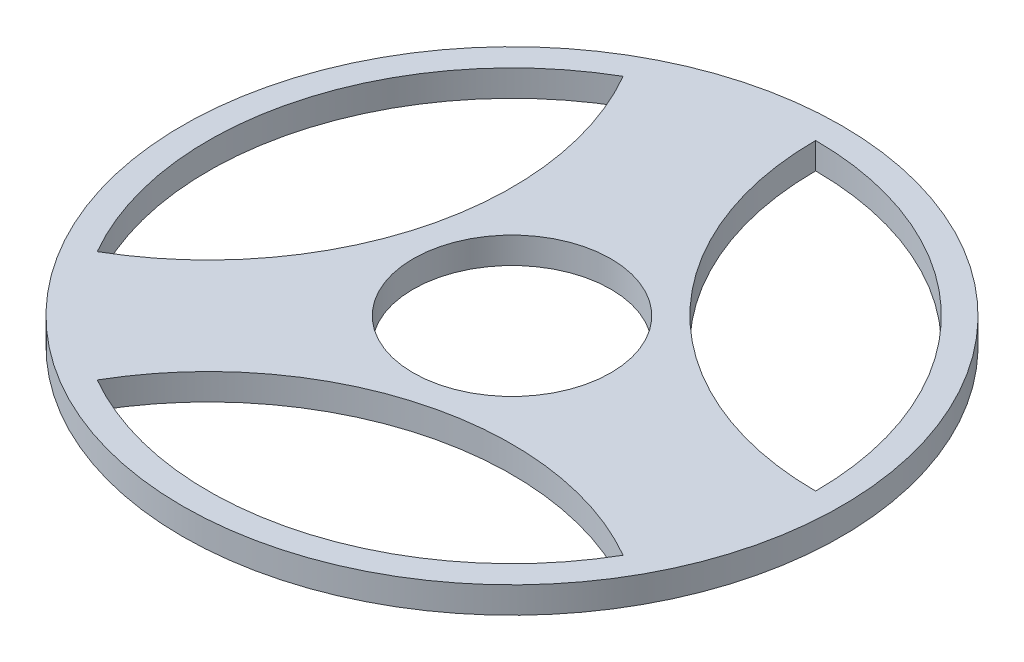
SolidWorks part; units mm, degrees
ref_plane "Alzado" through (0, 0, 0) normal (0, 0, 1) x (1, 0, 0)
ref_plane "Planta" through (0, 0, 0) normal (0, 1, 0) x (1, 0, 0)
ref_plane "Vista lateral" through (0, 0, 0) normal (1, 0, 0) x (0, 0, -1)
sketch "Croquis1" plane through (0, 0, 0) normal (0, 1, 0) x (1, 0, 0)
  line L0 (0, 0) -> (0, 150) construction
  line L2 (0, 500) -> (0, 542.3497) construction
  line L28 (0, 0) -> (460.6468, 0) construction
  line L29 (460.6468, 0) -> (460.6468, 460.6468) construction
  line L30 (460.6468, 460.6468) -> (0, 0) construction
  circle A0 centre (0, 0) radius 500
  circle A26 centre (0, 0) radius 150
  arc A27 (0, 460.6468) -> (460.6468, 0) centre (0, 0) cw
  arc A28 (0, 460.6468) -> (460.6468, 0) centre (460.6468, 460.6468) ccw
  arc A29 (398.9319, -230.3234) -> (-230.3234, -398.9319) centre (0, 0) cw
  arc A30 (398.9319, -230.3234) -> (-230.3234, -398.9319) centre (168.6084, -629.2553) ccw
  arc A31 (-398.9319, -230.3234) -> (-230.3234, 398.9319) centre (0, 0) cw
  arc A32 (-398.9319, -230.3234) -> (-230.3234, 398.9319) centre (-629.2553, 168.6084) ccw
  dimension "D1" = 1000
  dimension "D2" = 300
  dimension "D3" = 3
extrude "Saliente-Extruir1" add sketch "Croquis1" along normal blind 40 contours A0 A32 A31 A30 A29 A28 A27 A26
